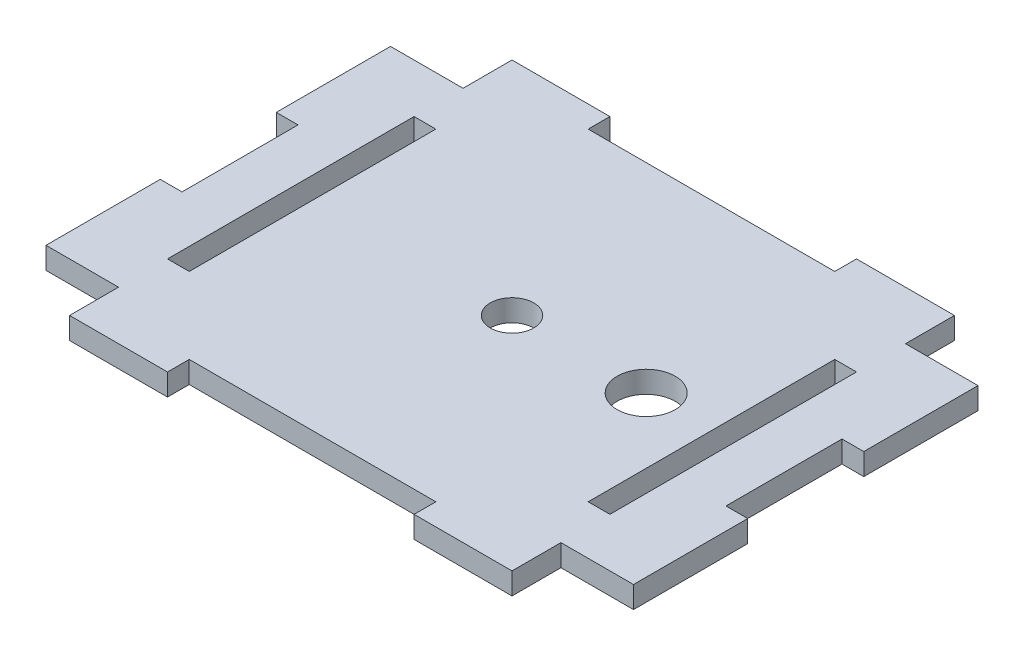
SolidWorks part; units mm, degrees
ref_plane "Alzado" through (0, 0, 0) normal (0, 0, 1) x (1, 0, 0)
ref_plane "Planta" through (0, 0, 0) normal (0, 1, 0) x (1, 0, 0)
ref_plane "Vista lateral" through (0, 0, 0) normal (1, 0, 0) x (0, 0, -1)
sketch "Croquis1" plane through (0, 0, 0) normal (0, 1, 0) x (1, 0, 0)
  line L0 (-27.5, 0) -> (-27.5, 17)
  line L1 (-27.5, 0) -> (-27.5, -17)
  line L2 (-27.5, -17) -> (-30.5, -17)
  line L3 (-30.5, -17) -> (-30.5, 17)
  line L4 (-30.5, 17) -> (-27.5, 17)
  line L5 (0, 27.5) -> (17, 27.5)
  line L6 (17, 30.5) -> (17, 27.5)
  line L7 (-30.5, 23.75) -> (-30.5, 30.5)
  line L8 (0, 27.5) -> (-17, 27.5)
  line L9 (-17, 27.5) -> (-17, 30.5)
  line L10 (27.5, 0) -> (27.5, -17)
  line L11 (30.5, -17) -> (27.5, -17)
  line L12 (30.5, 17) -> (30.5, -17)
  line L13 (27.5, 0) -> (27.5, 17)
  line L14 (27.5, 17) -> (30.5, 17)
  line L15 (0, -27.5) -> (-17, -27.5)
  line L16 (-17, -30.5) -> (-17, -27.5)
  line L17 (-30.5, 30.5) -> (-23.75, 30.5)
  line L18 (0, -27.5) -> (17, -27.5)
  line L19 (17, -27.5) -> (17, -30.5)
  line L20 (23.75, 30.5) -> (30.5, 30.5)
  line L21 (30.5, 30.5) -> (30.5, 23.75)
  line L22 (-37.5, 0) -> (-37.5, 8)
  line L23 (-37.5, 8) -> (-40.5, 8)
  line L24 (23.75, -30.5) -> (30.5, -30.5)
  line L25 (-40.5, -8) -> (-37.5, -8)
  line L26 (-37.5, -8) -> (-37.5, 0)
  line L27 (23.75, 30.5) -> (17, 30.5)
  line L28 (30.5, -30.5) -> (30.5, -17)
  line L29 (-30.5, 23.75) -> (-40.5, 23.75)
  line L30 (-40.5, 8) -> (-40.5, 23.75)
  line L31 (-23.75, -30.5) -> (-30.5, -30.5)
  line L32 (-23.75, 30.5) -> (-17, 30.5)
  line L33 (0, 0) -> (18.5, 0) construction
  line L34 (40.5, 8) -> (40.5, 23.75)
  line L35 (30.5, 23.75) -> (40.5, 23.75)
  line L36 (37.5, -8) -> (37.5, 0)
  line L37 (40.5, -8) -> (37.5, -8)
  line L38 (-30.5, -30.5) -> (-30.5, -23.75)
  line L39 (37.5, 8) -> (40.5, 8)
  line L40 (37.5, 0) -> (37.5, 8)
  line L41 (-40.5, -8) -> (-40.5, -23.75)
  line L42 (-30.5, -23.75) -> (-40.5, -23.75)
  line L44 (-23.75, -30.5) -> (-17, -30.5)
  line L45 (23.75, -30.5) -> (17, -30.5)
  line L47 (30.5, -23.75) -> (40.5, -23.75)
  line L48 (40.5, -8) -> (40.5, -23.75)
  line L49 (17, -30.5) -> (-17, -30.5) [skipped]
  line L50 (-17, 30.5) -> (17, 30.5) [skipped]
  circle A0 centre (0, 0) radius 27.5 construction
  circle A1 centre (0, 0) radius 3
  circle A2 centre (0, 0) radius 23.5 construction
  circle A3 centre (18.5, 0) radius 4
  point P27 (0, 0)
  dimension "D1" = 55
  dimension "D2" = 6
  dimension "D7" = 47
  dimension "D12" = 8
  dimension "D3" = 17
  dimension "D4" = 17
  dimension "D5" = 3
  dimension "D8" = 37.5
  dimension "D9" = 8
  dimension "D10" = 3
  dimension "D11" = 16
  dimension "D13" = 18.5
  dimension "D6" = 4
extrude "Saliente-Extruir1" add sketch "Croquis1" along normal blind 3
